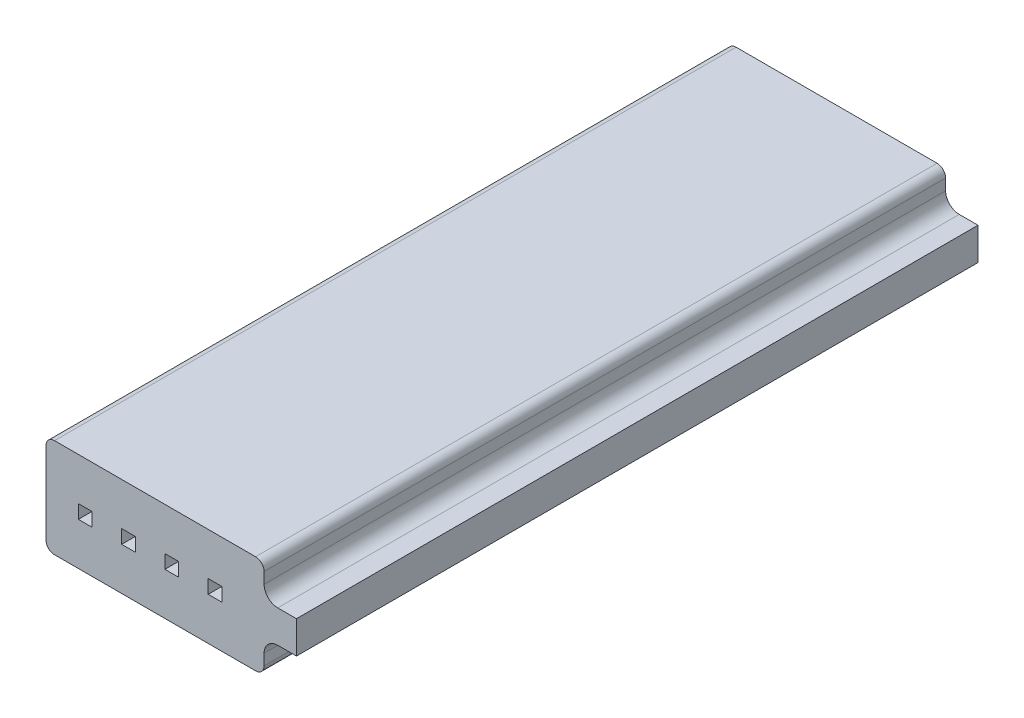
SolidWorks part; units mm, degrees
ref_plane "Plan de face" through (0, 0, 0) normal (0, 0, 1) x (1, 0, 0)
ref_plane "Plan de dessus" through (0, 0, 0) normal (0, 1, 0) x (1, 0, 0)
ref_plane "Plan de droite" through (0, 0, 0) normal (1, 0, 0) x (0, 0, -1)
sketch "Esquisse1" plane through (0, 0, 0) normal (0, 0, 1) x (1, 0, 0)
  line L0 (6.4, 0.95) -> (8.3, 0.95)
  line L1 (-6.4, 2.9) -> (6.4, 2.9)
  line L2 (-6.4, 2.9) -> (-6.4, -2.9)
  line L3 (-6.4, -2.9) -> (6.4, -2.9)
  line L4 (6.4, 2.9) -> (6.4, -2.9) construction
  line L5 (-6.4, 2.9) -> (6.4, -2.9) construction
  line L6 (-6.4, -2.9) -> (6.4, 2.9) construction
  line L7 (8.3, 0.95) -> (8.3, -0.95)
  line L8 (8.3, -0.95) -> (6.4, -0.95)
  line L9 (6.4, 2.9) -> (6.4, 0.95)
  line L10 (6.4, -0.95) -> (6.4, -2.9)
  line L11 (8.3, 0) -> (6.4, 0) construction
  point P0 (0, 0)
  dimension "D1" = 12.8
  dimension "D2" = 5.8
  dimension "D3" = 1.9
  dimension "D4" = 1.9
extrude "Boss.-Extru.1" add sketch "Esquisse1" along normal blind 40
sketch "Esquisse3" plane through (0, 0, 0) normal (0, 0, -1) x (-1, 0, 0)
  line L0 (6.4, 0) -> (4.1, 0) construction
  line L1 (6.4, 2.9) -> (6.4, -2.9) construction
  line L3 (3.7, 0.4) -> (4.5, 0.4)
  line L4 (3.7, 0.4) -> (3.7, -0.4)
  line L5 (3.7, -0.4) -> (4.5, -0.4)
  line L6 (4.5, 0.4) -> (4.5, -0.4)
  line L7 (3.7, 0.4) -> (4.5, -0.4) construction
  line L8 (3.7, -0.4) -> (4.5, 0.4) construction
  dimension "D1" = 0.8
  dimension "D2" = 0.8
  dimension "D3" = 2.3
extrude "Enlèv. mat.-Extru.1" cut sketch "Esquisse3" against normal through all
pattern_linear "Répétition linéaire1" count 4 spacing 2.54 along (1, 0, 0) of "Enlèv. mat.-Extru.1"
fillet "Congé1" radius 0.8 2 edges at (6.4, -0.95, 20) (6.4, 0.95, 20)
fillet "Congé2" radius 0.5 4 edges at (-6.4, -2.9, 20) (6.4, -2.9, 20) (6.4, 2.9, 20) (-6.4, 2.9, 20)
